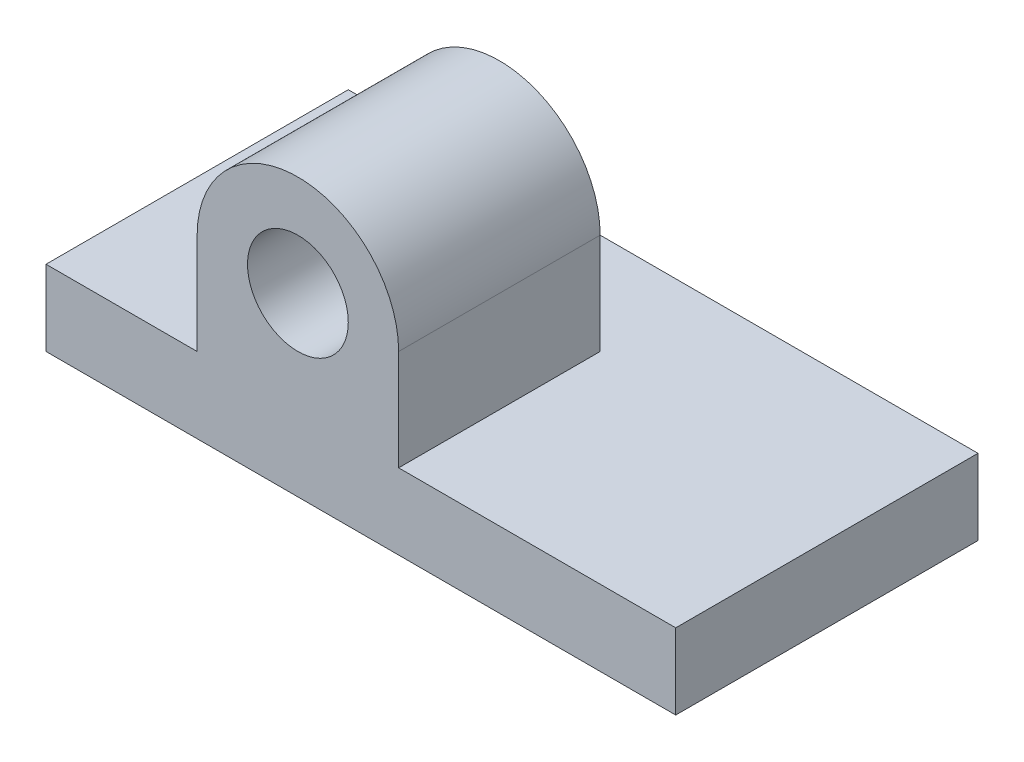
SolidWorks part; units mm, degrees
ref_plane "Front Plane" through (0, 0, 0) normal (0, 0, 1) x (1, 0, 0)
ref_plane "Top Plane" through (0, 0, 0) normal (0, 1, 0) x (1, 0, 0)
ref_plane "Right Plane" through (0, 0, 0) normal (1, 0, 0) x (0, 0, -1)
sketch "Sketch1" plane through (0, 0, 0) normal (0, 0, 1) x (1, 0, 0)
  line L0 (30, 35) -> (30, 15)
  line L1 (0, 0) -> (125, 0)
  line L2 (0, 0) -> (0, 15)
  line L3 (0, 15) -> (30, 15)
  line L4 (125, 0) -> (125, 15)
  line L5 (70, 35) -> (70, 15)
  line L6 (70, 15) -> (125, 15)
  circle A0 centre (50, 35) radius 10
  arc A1 (70, 35) -> (30, 35) centre (50, 35) ccw
  point P12 (50, 40.0704)
  dimension "D3" = 40
  dimension "D4" = 20
  dimension "D5" = 50
  dimension "D6" = 35
  dimension "D1" = 125
  dimension "D2" = 15
extrude "Boss-Extrude1" add sketch "Sketch1" against normal blind 60
sketch "Sketch2" plane through (0, 0, 0) normal (1, 0, 0) x (0, 0, -1)
  line L0 (60, 55) -> (0, 55) construction
  line L1 (60, 15) -> (40, 15)
  line L2 (60, 15) -> (60, 55)
  line L3 (60, 55) -> (40, 55)
  line L4 (40, 15) -> (40, 55)
  dimension "D1" = 20
extrude "Cut-Extrude1" cut sketch "Sketch2" along normal through all
